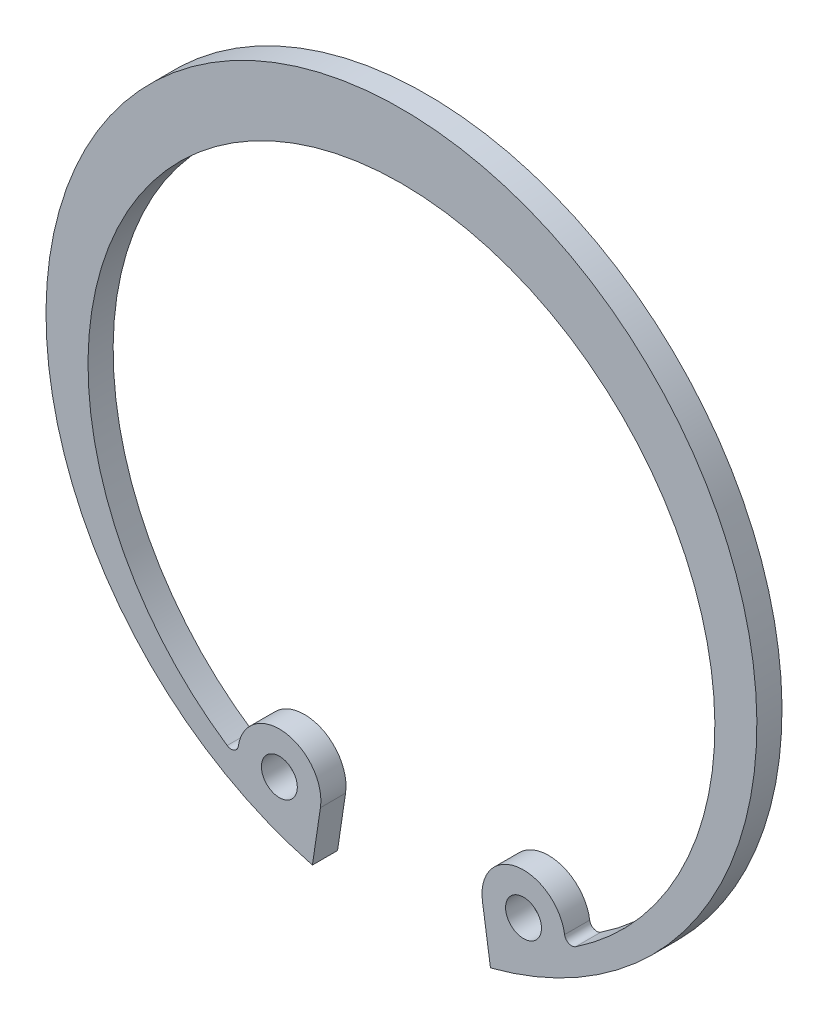
SolidWorks part; units mm, degrees
ref_plane "Front Plane" through (0, 0, 0) normal (0, 0, 1) x (1, 0, 0)
ref_plane "Top Plane" through (0, 0, 0) normal (0, 1, 0) x (1, 0, 0)
ref_plane "Right Plane" through (0, 0, 0) normal (1, 0, 0) x (0, 0, -1)
sketch "Sketch1" plane through (0, 0, 0) normal (0, 0, 1) x (1, 0, 0)
  line L0 (0, 0) -> (0, 24.75) construction
  line L1 (-5.6409, -20.2201) -> (-6.2, -23.9609)
  line L2 (5.6409, -20.2201) -> (6.2, -23.9609)
  line L3 (7.3593, -17.1366) -> (9.7663, -22.7416) construction
  arc A0 (6.2, -23.9609) -> (-6.2, -23.9609) centre (0, 0) ccw
  arc A1 (-12.1329, -19.7167) -> (-11.3603, -19.3736) centre (-11.855, -19.3011) ccw
  circle A2 centre (-8.5, -19.7928) radius 1.25
  circle A3 centre (8.5, -19.7928) radius 1.25
  circle A4 centre (0, 0) radius 17 construction
  arc A6 (-5.6409, -20.2201) -> (-11.3603, -19.3736) centre (-8.5, -19.7928) ccw
  arc A7 (11.3603, -19.3736) -> (5.6409, -20.2201) centre (8.5, -19.7928) ccw
  arc A8 (12.1329, -19.7167) -> (-12.1329, -19.7167) centre (0, -1.575) ccw
  arc A9 (12.1329, -19.7167) -> (11.3603, -19.3736) centre (11.855, -19.3011) cw
  point P13 (0, 20.25)
  dimension "D1" = 0.5
  dimension "RIC_D2_s" = 49.5
  dimension "D2" = 17
  dimension "RIC_D4_s" = 43.65
  dimension "RIC_D0_s" = 2.5
  dimension "RIC_D5_s" = 34
  dimension "RIC_B_s" = 4.5
  dimension "RIC_MSM_2" = 17
  dimension "RIC_MSM_1" = 12.4
  dimension "RIC_A_s" = 6.1
extrude "Boss-Extrude1" add sketch "Sketch1" along normal blind 1.75
equation "\"RIC_D4_s@Sketch1\"=\"RIC_D2_s@Sketch1\"-1.3*\"RIC_B_s@Sketch1\""
